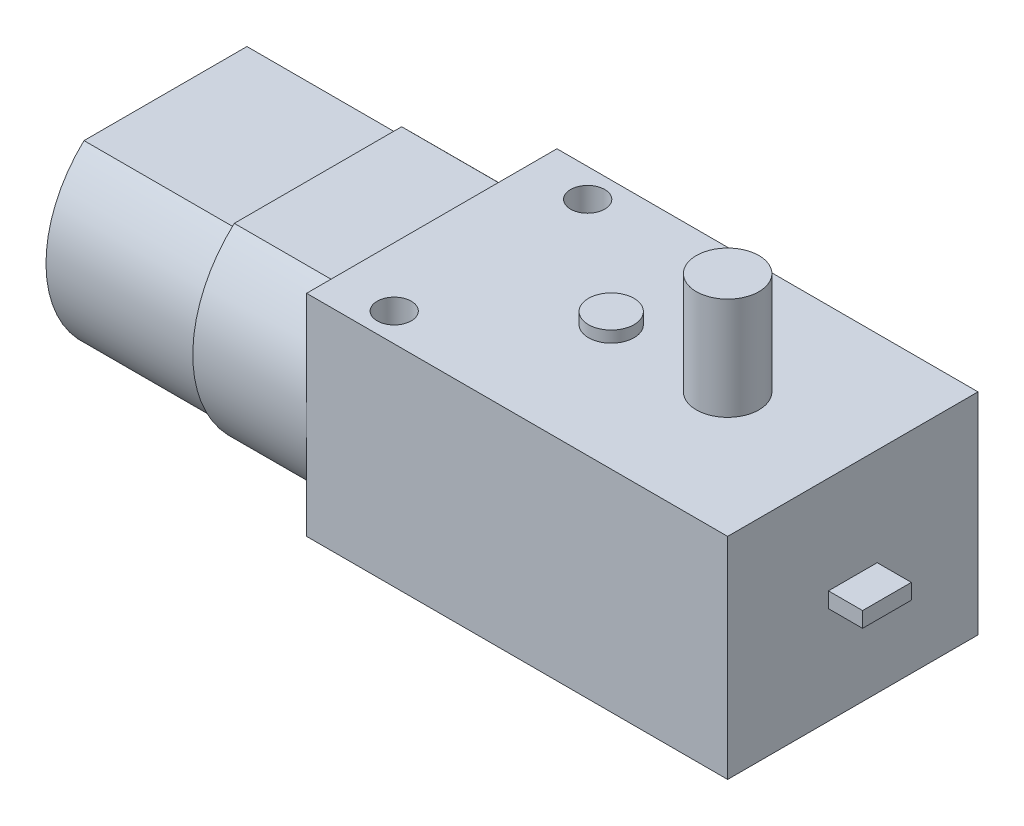
SolidWorks part; units mm, degrees
ref_plane "정면" through (0, 0, 0) normal (0, 0, 1) x (1, 0, 0)
ref_plane "윗면" through (0, 0, 0) normal (0, 1, 0) x (1, 0, 0)
ref_plane "우측면" through (0, 0, 0) normal (1, 0, 0) x (0, 0, -1)
sketch "스케치1" plane through (0, 0, 0) normal (0, 0, 1) x (1, 0, 0)
  line L0 (-18.5, 9.25) -> (-18.5, -9.25)
  line L1 (-18.5, 9.25) -> (18.5, 9.25)
  line L3 (-18.5, -9.25) -> (18.5, -9.25)
  line L4 (18.5, 9.25) -> (18.5, -9.25)
  point P8 (18.5, 0)
  point P9 (0, 9.25)
  dimension "D1" = 18.5
  dimension "D2" = 37
extrude "보스-돌출1" add sketch "스케치1" along normal mid plane 22
sketch "스케치2" plane through (-18.5, 0, 0) normal (-1, 0, 0) x (0, 0, 1)
  line L0 (-6.2252, -9.5) -> (6.2252, -9.5)
  line L5 (-7.3533, 7.75) -> (7.3533, 7.75)
  line L8 (11, 9.25) -> (-11, 9.25) construction
  arc A0 (6.2252, -9.5) -> (7.3533, 7.75) centre (0, -0.431) ccw
  arc A1 (-7.3533, 7.75) -> (-6.2252, -9.5) centre (0, -0.431) ccw
  dimension "D1" = 1.5
  dimension "D2" = 11
extrude "보스-돌출2" add sketch "스케치2" along normal blind 10
sketch "스케치3" plane through (-28.5, 0, 0) normal (-1, 0, 0) x (0, 0, 1)
  line L4 (-6.0681, -9) -> (6.0681, -9)
  line L5 (7.1591, 7.25) -> (-7.1591, 7.25)
  line L6 (-6.0681, -9) -> (6.0681, -9)
  line L7 (7.1591, 7.25) -> (-7.1591, 7.25)
  arc A4 (-7.1591, 7.25) -> (-6.0681, -9) centre (0, -0.431) ccw
  arc A5 (6.0681, -9) -> (7.1591, 7.25) centre (0, -0.431) ccw
  arc A6 (-7.1591, 7.25) -> (-6.0681, -9) centre (0, -0.431) ccw
  arc A7 (6.0681, -9) -> (7.1591, 7.25) centre (0, -0.431) ccw
  dimension "D1" = 0.5
extrude "보스-돌출3" add sketch "스케치3" along normal blind 13.4
sketch "스케치4" plane through (18.5, 0, 0) normal (1, 0, 0) x (0, 0, -1)
  line L1 (2.1427, 0.6773) -> (-2.1427, 0.6773)
  line L2 (2.1427, 0.6773) -> (2.1427, -0.6773)
  line L3 (2.1427, -0.6773) -> (-2.1427, -0.6773)
  line L4 (-2.1427, 0.6773) -> (-2.1427, -0.6773)
  line L5 (2.1427, 0.6773) -> (-2.1427, -0.6773) construction
  line L6 (2.1427, -0.6773) -> (-2.1427, 0.6773) construction
  point P0 (0, 0)
extrude "보스-돌출4" add sketch "스케치4" along normal blind 3
sketch "스케치5" plane through (0, 9.25, 0) normal (0, 1, 0) x (1, 0, 0)
  line L0 (-16, 0) -> (18.5, 0) construction
  line L2 (18.5, 2.1427) -> (18.5, -2.1427) construction
  circle A0 centre (-2.729, 0) radius 2
  dimension "D1" = 4
extrude "보스-돌출5" add sketch "스케치5" along normal blind 1
sketch "스케치6" plane through (0, 9.25, 0) normal (0, 1, 0) x (1, 0, 0)
  line L0 (-18.5, 8.5) -> (18.5, 8.5) construction
  line L1 (-18.5, 11) -> (-18.5, 7.3533) construction
  line L2 (18.5, -11) -> (18.5, 11) construction
  line L3 (-13.3, 11) -> (-13.3, -11) construction
  line L4 (18.5, 11) -> (-18.5, 11) construction
  line L5 (18.5, -11) -> (-18.5, -11) construction
  line L6 (-16, 0) -> (18.5, 0) construction
  circle A0 centre (-13.3, 8.5) radius 1.5
  circle A1 centre (-13.3, -8.5) radius 1.5
  point P12 (-13.3, 8.5)
  point P21 (-13.3, 10)
  point P22 (-14.8, 8.5)
  dimension "D1" = 3
  dimension "D2" = 3.7
  dimension "D3" = 1
extrude "컷-돌출1" cut sketch "스케치6" against normal blind 20
sketch "스케치7" plane through (-41.9, 0, 0) normal (-1, 0, 0) x (0, 0, 1)
  line L4 (-6.0681, -9) -> (6.0681, -9)
  line L5 (7.1591, 7.25) -> (-7.1591, 7.25)
  line L6 (-6.0681, -9) -> (6.0681, -9)
  line L7 (7.1591, 7.25) -> (-7.1591, 7.25)
  arc A4 (-7.1591, 7.25) -> (-6.0681, -9) centre (0, -0.431) ccw
  arc A5 (6.0681, -9) -> (7.1591, 7.25) centre (0, -0.431) ccw
  arc A6 (-7.1591, 7.25) -> (-6.0681, -9) centre (0, -0.431) ccw
  arc A7 (6.0681, -9) -> (7.1591, 7.25) centre (0, -0.431) ccw
  dimension "D1" = 0
sketch "스케치8" plane through (0, 9.25, 0) normal (0, 1, 0) x (1, 0, 0)
  line L0 (18.5, -11) -> (18.5, 11) construction
  circle A0 centre (7.5, 0) radius 2.75
  dimension "D1" = 5.5
  dimension "D2" = 11
extrude "보스-돌출6" add sketch "스케치8" along normal blind 9
